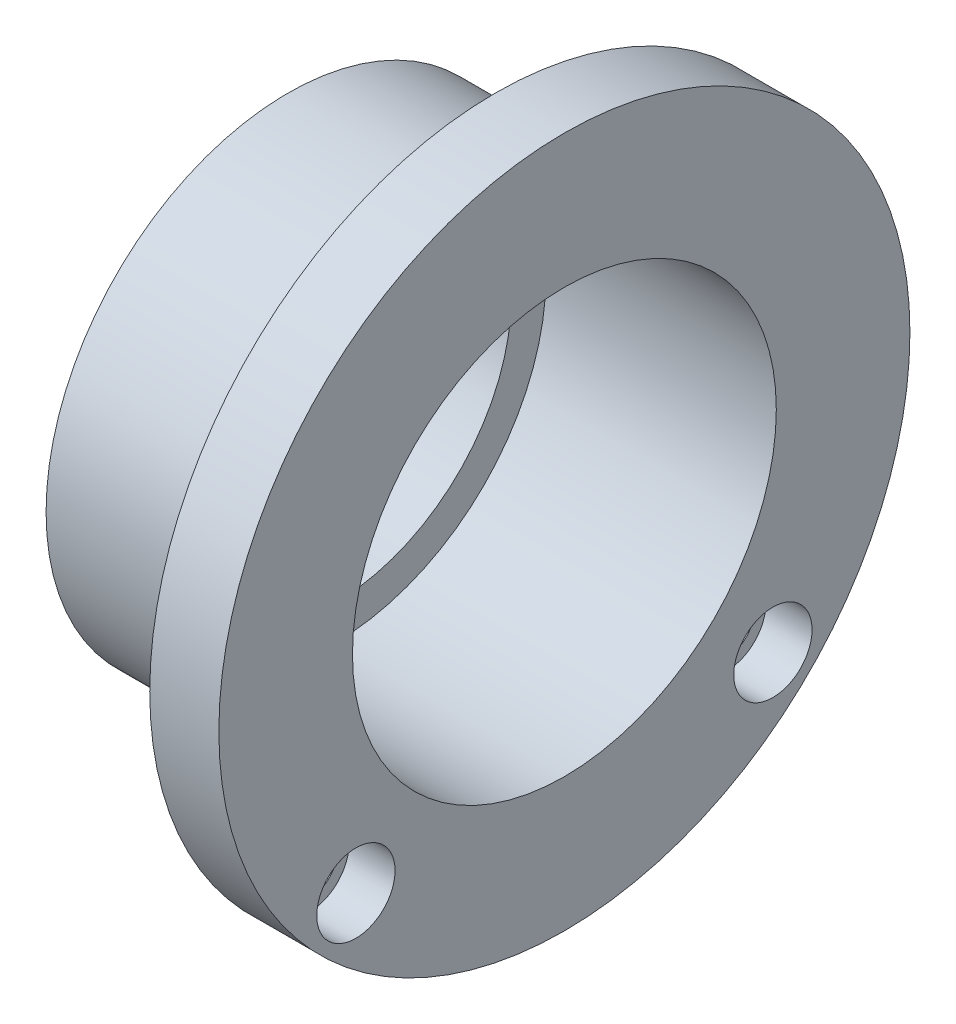
SolidWorks part; units mm, degrees
material "ASTM A36 Steel"
ref_plane "Front Plane" through (0, 0, 0) normal (0, 0, 1) x (1, 0, 0)
ref_plane "Top Plane" through (0, 0, 0) normal (0, 1, 0) x (1, 0, 0)
ref_plane "Right Plane" through (0, 0, 0) normal (1, 0, 0) x (0, 0, -1)
sketch "Sketch1" plane through (0, 0, 0) normal (0, 0, 1) x (1, 0, 0)
  line L0 (-100.1582, -16.3766) -> (-100.1582, -2.3766)
  line L1 (-100.1582, -2.3766) -> (-55.1582, -2.3766)
  line L2 (-55.1582, -2.3766) -> (-55.1582, 20.1234)
  line L3 (-55.1582, 20.1234) -> (-40.1582, 20.1234)
  line L4 (-40.1582, 20.1234) -> (-40.1582, -8.8766)
  line L5 (-40.1582, -8.8766) -> (-90.1582, -8.8766)
  line L6 (-90.1582, -8.8766) -> (-90.1582, -16.3766)
  line L7 (-90.1582, -16.3766) -> (-100.1582, -16.3766)
  line L8 (-100.1582, -54.8766) -> (40.8228, -54.8766)
  dimension "D1" = 38.5
  dimension "D2" = 7.5
  dimension "D3" = 10
  dimension "D4" = 50
  dimension "D5" = 15
  dimension "D6" = 75
  dimension "D7" = 52.5
revolve "Revolve1" add sketch "Sketch1" angle 360 about L8
sketch "Sketch3" plane through (-40.1582, 0, 0) normal (1, 0, 0) x (0, 0, -1)
  circle A1 centre (45.2548, -100.1314) radius 6
  circle A2 centre (-45.2548, -100.1314) radius 6
  dimension "D2" = 12
extrude "Cut-Extrude2" cut sketch "Sketch3" against normal blind 16
sketch "Sketch4" plane through (-40.1582, 0, 0) normal (1, 0, 0) x (0, 0, -1)
  circle A0 centre (-45.2548, -100.1314) radius 8.5
  circle A1 centre (45.2548, -100.1314) radius 8.5
  dimension "D1" = 17
  dimension "D2" = 17
extrude "Cut-Extrude3" cut sketch "Sketch4" against normal blind 10
